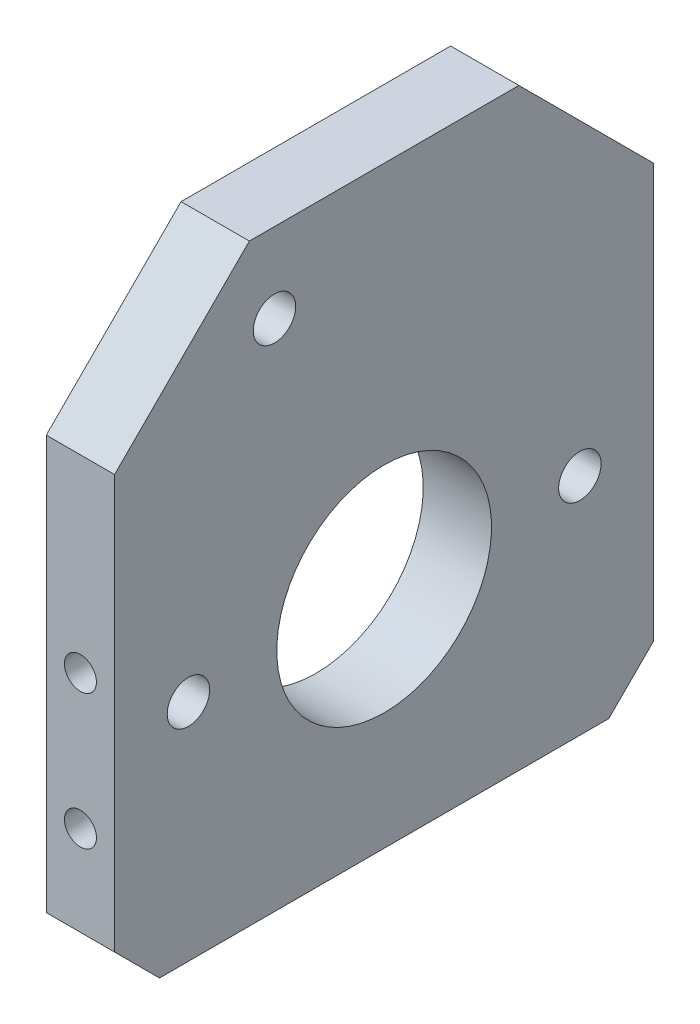
SolidWorks part; units mm, degrees
material "1060 Alloy"
ref_plane "Front" through (0, 0, 0) normal (0, 0, 1) x (1, 0, 0)
ref_plane "Top" through (0, 0, 0) normal (0, 1, 0) x (1, 0, 0)
ref_plane "Right" through (0, 0, 0) normal (1, 0, 0) x (0, 0, -1)
sketch "Sketch1" plane through (0, 0, 0) normal (1, 0, 0) x (0, 0, -1)
  line L0 (20.1279, -11.6427) -> (-11.6221, -11.6427) construction
  line L1 (-14.7971, 30.2823) -> (23.3029, 30.2823)
  line L2 (-14.7971, 30.2823) -> (-14.7971, -11.6427)
  line L3 (-14.7971, -11.6427) -> (23.3029, -11.6427)
  line L4 (23.3029, 30.2823) -> (23.3029, -11.6427)
  circle A1 centre (4.2529, 11.2323) radius 18.5 construction
  circle A5 centre (4.2529, 4.2323) radius 7.5875
  circle A6 centre (4.2529, 4.2323) radius 7.5875
  dimension "D1" = 19.05
  dimension "D2" = 19.05
  dimension "D3" = 19.05
  dimension "D5" = 1.5875
extrude "Boss-Extrude1" add sketch "Sketch1" along normal blind 4.826
hole_wizard "Ø3.0 (3) Diameter Hole1" positions "Sketch2" profile "Sketch3" hole size "Ø3.0" standard "ANSI Metric" end condition through all
sketch "Sketch2" plane through (0, 0, 0) normal (-1, 0, 0) x (0, 0, 1)
  point P0 (3.4971, 24.6557)
  point P3 (9.5764, 4.2323)
  point P6 (-18.0822, 4.2323)
sketch "Sketch3" plane through (0, 24.6557, 3.4971) normal (0, 1, 0) x (0, 0, 1)
  line L0 (0, 0) -> (0, 4.826)
  line L1 (0, 4.826) -> (1.5, 4.826)
  line L2 (1.5, 4.826) -> (1.5, 0)
  line L5 (1.5, 0) -> (0, 0)
  line L11 (0, -6.35) -> (0, 107.95) construction
  dimension "Thru Hole Dia." = 3
  dimension "Thru Hole Depth" = 4.826
chamfer "Chamfer1" distance 9.525 angle 45 2 edges at (2.413, 30.2823, -23.3029) (2.413, 30.2823, 14.7971)
chamfer "Chamfer2" distance 3.175 angle 45 2 edges at (2.413, -11.6427, 14.7971) (2.413, -11.6427, -23.3029)
hole_wizard "#4-40 Tapped Hole1" positions "Sketch4" profile "Sketch5" tap size "#4-40" standard "ANSI Inch"
sketch "Sketch4" plane through (-40.9593, -24.0447, -23.3029) normal (0, 0, -1) x (-1, 0, 0)
  point P0 (-43.3723, 31.452)
  point P1 (-43.3723, 21.927)
  point P4 (0, 0)
  point P5 (0, 0)
sketch "Sketch5" plane through (2.413, 7.4073, -23.3029) normal (1, 0, 0) x (0, 1, 0)
  line L0 (0, 0) -> (0, 8.2992)
  line L1 (0, 8.2992) -> (1.1303, 7.62)
  line L2 (1.1303, 7.62) -> (1.1303, 0)
  line L5 (1.1303, 0) -> (0, 0)
  line L10 (0, 8.2992) -> (-1.1303, 7.62) construction
  line L11 (0, -6.35) -> (0, 107.95) construction
  dimension "Tap Drill Dia." = 2.2606
  dimension "Tap Drill Depth" = 7.62
  dimension "Drill Angle" = 118
cosmetic thread "Hole Thread1" parameters "D1"=5.588, "D2"=2.8448
cosmetic thread "Hole Thread2" parameters "D1"=5.588, "D2"=2.8448
hole_wizard "#4-40 Tapped Hole2" positions "Sketch6" profile "Sketch7" tap size "#4-40" standard "ANSI Inch"
sketch "Sketch6" plane through (-40.9593, -24.0447, 14.7971) normal (0, 0, 1) x (1, 0, 0)
  point P0 (43.3723, 21.927)
  point P1 (43.3723, 31.452)
cosmetic thread "Hole Thread3" parameters "D1"=5.588, "D2"=2.8448
cosmetic thread "Hole Thread4" parameters "D1"=5.588, "D2"=2.8448
sketch "Sketch7" plane through (2.413, -2.1177, 14.7971) normal (1, 0, 0) x (0, -1, 0)
  line L0 (0, 0) -> (0, 8.2992)
  line L1 (0, 8.2992) -> (1.1303, 7.62)
  line L2 (1.1303, 7.62) -> (1.1303, 0)
  line L5 (1.1303, 0) -> (0, 0)
  line L10 (0, 8.2992) -> (-1.1303, 7.62) construction
  line L11 (0, -6.35) -> (0, 107.95) construction
  dimension "Tap Drill Dia." = 2.2606
  dimension "Tap Drill Depth" = 7.62
  dimension "Drill Angle" = 118
